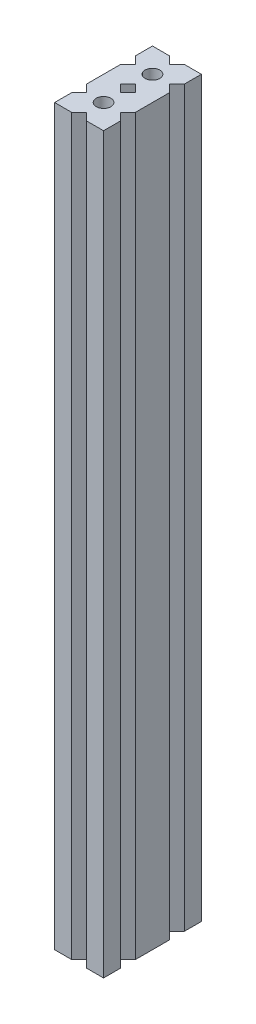
SolidWorks part; units mm, degrees
ref_plane "Front" through (0, 0, 0) normal (0, 0, 1) x (1, 0, 0)
ref_plane "Top" through (0, 0, 0) normal (0, 1, 0) x (1, 0, 0)
ref_plane "Right" through (0, 0, 0) normal (1, 0, 0) x (0, 0, -1)
sketch "Skizze1" plane through (0, 0, 0) normal (0, 1, 0) x (1, 0, 0)
  line L0 (0, 0) -> (0, 40)
  line L1 (0, 40) -> (20, 40)
  line L2 (20, 40) -> (20, 0)
  line L3 (20, 0) -> (0, 0)
  dimension "D1" = 20
  dimension "D2" = 40
extrude "Aufsatz-Linear austragen1" add sketch "Skizze1" along normal blind 300
sketch "Skizze2" plane through (0, 300, 0) normal (0, 1, 0) x (1, 0, 0)
  line L0 (10, 40) -> (10, 20) construction
  line L1 (0, 30) -> (20, 30) construction
  line L2 (7, 40) -> (10, 37)
  line L3 (13, 40) -> (10, 37)
  line L4 (10, 30) -> (20, 40) construction
  line L5 (7, 40) -> (13, 40)
  line L6 (20, 33) -> (17, 30)
  line L7 (20, 27) -> (17, 30)
  line L8 (20, 27) -> (20, 33)
  line L9 (0, 27) -> (0, 33)
  line L10 (0, 27) -> (3, 30)
  line L11 (0, 33) -> (3, 30)
  line L12 (7, 20) -> (13, 20)
  line L13 (13, 20) -> (10, 23)
  line L14 (7, 20) -> (10, 23)
  line L15 (0, 20) -> (20, 20) construction
  line L16 (0, 40) -> (0, 0) construction
  line L17 (20, 0) -> (20, 40) construction
  line L18 (20, 40) -> (0, 40) construction
  line L19 (7, 20) -> (10, 17)
  line L20 (13, 20) -> (10, 17)
  line L21 (20, 13) -> (17, 10)
  line L22 (20, 7) -> (17, 10)
  line L23 (20, 13) -> (20, 7)
  line L24 (13, 0) -> (10, 3)
  line L25 (7, 0) -> (13, 0)
  line L26 (7, 0) -> (10, 3)
  line L27 (0, 13) -> (3, 10)
  line L28 (0, 13) -> (0, 7)
  line L29 (0, 7) -> (3, 10)
  line M14 (0, 0) -> (20, 0)
  line M15 (20, 0) -> (20, 40)
  line M16 (20, 40) -> (0, 40)
  line M17 (0, 40) -> (0, 0)
  dimension "D1" = 3
  dimension "D2" = 3
extrude "Schnitt-Linear austragen1" cut sketch "Skizze2" against normal through all contours L11 L10 M17 | L3 L2 M16 | L7 L6 M15 | L20 L12 L19 | L14 L12 L13 | L22 L21 M15 | L29 L27 M17 | L26 L24 M14
ref_plane "Ebene1" through (0, 150, 0) normal (0, 1, 0) x (1, 0, 0)
sketch "Skizze3" plane through (0, 0, 0) normal (0, -1, 0) x (1, 0, 0)
  line L0 (10, -3) -> (10, -17) construction
  line L1 (20, -20) -> (0, -20) construction
  line L2 (20, -13) -> (20, -27) construction
  line L3 (0, -27) -> (0, -13) construction
  circle A0 centre (10, -10) radius 3
  circle A1 centre (10, -30) radius 3
  dimension "D1" = 6
extrude "Schnitt-Linear austragen2" cut sketch "Skizze3" against normal through all
